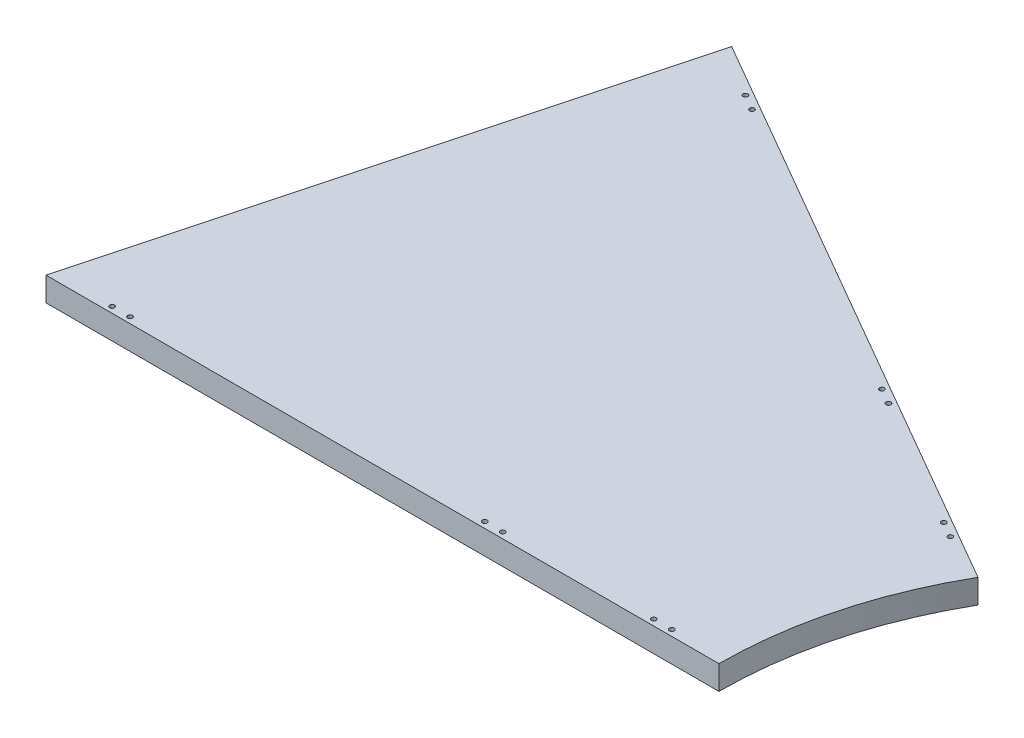
SolidWorks part; units mm, degrees
ref_plane "Front Plane" through (0, 0, 0) normal (0, 0, 1) x (1, 0, 0)
ref_plane "Top Plane" through (0, 0, 0) normal (0, 1, 0) x (1, 0, 0)
ref_plane "Right Plane" through (0, 0, 0) normal (1, 0, 0) x (0, 0, -1)
sketch "Sketch1" plane through (0, 0, 0) normal (0, 1, 0) x (1, 0, 0)
  line L0 (-340, 0) -> (-900, 0)
  line L1 (-294.4486, 170) -> (-779.4229, 450)
  line L2 (-779.4229, 450) -> (-900, 0)
  arc A1 (-294.4486, 170) -> (-340, 0) centre (0, 0) ccw
  dimension "D1" = 900
  dimension "D2" = 900
  dimension "D3" = 30
extrude "Boss-Extrude1" add sketch "Sketch1" along normal blind 20
sketch "Sketch2" plane through (0, 0, 0) normal (0, -1, 0) x (1, 0, 0)
  line L0 (-900, 0) -> (-340, 0) construction
  line L3 (0, 0) -> (-960.9334, -257.4813) construction
  circle A0 centre (-850, -5) radius 2
  circle A1 centre (-835, -5) radius 2
  circle A2 centre (-539.91, -5) radius 2
  circle A3 centre (-524.91, -5) radius 2
  circle A4 centre (-399.25, -5) radius 2
  circle A5 centre (-384.25, -5) radius 2
  circle A6 centre (-348.2606, -195.2949) radius 2
  circle A7 centre (-335.2703, -187.7949) radius 2
  circle A8 centre (-457.0854, -258.1249) radius 2
  circle A9 centre (-470.0758, -265.6249) radius 2
  circle A10 centre (-725.6312, -413.1699) radius 2
  circle A11 centre (-738.6216, -420.6699) radius 2
  point P0 (-850, 0)
  point P1 (-539.91, 0)
  point P5 (-399.25, 0)
  dimension "D4" = 4
  dimension "D5" = 4
  dimension "D6" = 4
  dimension "D7" = 4
  dimension "D8" = 4
  dimension "D9" = 4
  dimension "D1" = 50
  dimension "D2" = 360.09
  dimension "D3" = 500.75
  dimension "D10" = 5
  dimension "D11" = 5
  dimension "D12" = 15
  dimension "D13" = 5
  dimension "D14" = 5
  dimension "D15" = 15
  dimension "D16" = 5
  dimension "D17" = 5
  dimension "D18" = 15
  dimension "D19" = 15
extrude "Cut-Extrude1" cut sketch "Sketch2" against normal blind 20
